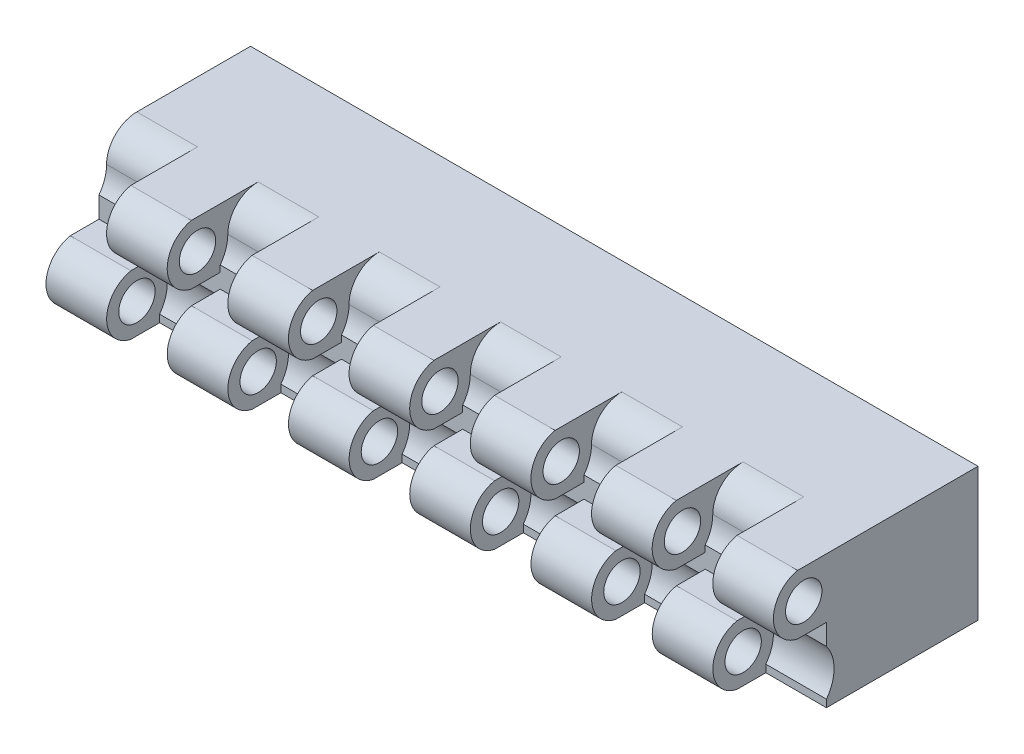
SolidWorks part; units mm, degrees
ref_plane "Front Plane" through (0, 0, 0) normal (0, 0, 1) x (1, 0, 0)
ref_plane "Top Plane" through (0, 0, 0) normal (0, 1, 0) x (1, 0, 0)
ref_plane "Right Plane" through (0, 0, 0) normal (1, 0, 0) x (0, 0, -1)
sketch "Sketch1" plane through (0, 0, 0) normal (1, 0, 0) x (0, 0, -1)
  line L1 (-12.5, 11) -> (12.5, 11)
  line L2 (-12.5, 11) -> (-12.5, -11)
  line L3 (-12.5, -11) -> (12.5, -11)
  line L4 (12.5, 11) -> (12.5, -11)
  line L5 (-12.5, 11) -> (12.5, -11) construction
  line L6 (-12.5, -11) -> (12.5, 11) construction
  point P0 (0, 0)
  dimension "D1" = 22
  dimension "D2" = 25
extrude "Boss-Extrude1" add sketch "Sketch1" along normal mid plane 120
sketch "Sketch5" plane through (60, 0, 0) normal (1, 0, 0) x (0, 0, -1)
  line L0 (-12.5, 11) -> (-12.5, 1.01) construction
  line L1 (-12.5, 11) -> (-12.5, -11) construction
  line L2 (-12.5, 6.005) -> (-17.5, 6.005) construction
  line L3 (-13.7433, 11) -> (-11.25, 11)
  line L7 (-11.25, 6.005) -> (-11.25, 11)
  arc A1 (-13.7433, 11) -> (-11.25, 6.005) centre (-17.5, 6.005) ccw
  dimension "D1" = 5
extrude "Cut-Extrude2" cut sketch "Sketch5" against normal up to next
sketch "Sketch6" plane through (-60, 0, 0) normal (-1, 0, 0) x (0, 0, 1)
  line L0 (12.5, -11) -> (12.5, -1.01) construction
  line L1 (12.5, 2.255) -> (12.5, -11) construction
  line L2 (12.5, -6.005) -> (17.5, -6.005) construction
  circle A0 centre (17.5, -6.005) radius 6.26
  dimension "D2" = 5
  dimension "D1" = 9.99
extrude "Cut-Extrude3" cut sketch "Sketch6" against normal up to next
fillet "Fillet1" radius 5 1 edges at (0, 11, 11.25)
sketch "Sketch2" plane through (60, 0, 0) normal (1, 0, 0) x (0, 0, -1)
  line L0 (-17.25, 1.202) -> (-6, 1.202)
  line L1 (-12.5, -11) -> (-12.5, 1.202) construction
  line L13 (-6, 11) -> (-6, 1.202)
  line L14 (-17.25, 11) -> (-6, 11)
  line L16 (12.5, 11) -> (-6.25, 11) construction
  arc A1 (-17.25, 11) -> (-17.25, 1.202) centre (-16.25, 6.101) ccw
  circle A2 centre (-16.25, 6.101) radius 3
  dimension "D3" = 6
  dimension "D1" = 10.25
  dimension "D5" = 5
  dimension "D2" = 11.25
  dimension "D4" = 5
extrude "Boss-Extrude2" add sketch "Sketch2" against normal blind 10
pattern_linear "LPattern1" count 6 spacing 20 along (-1, 0, 0) of "Boss-Extrude2"
sketch "Sketch3" plane through (-60, 0, 0) normal (-1, 0, 0) x (0, 0, 1)
  line L0 (10.99, -1.202) -> (17.24, -1.202)
  line L1 (17.24, -11) -> (10.99, -11)
  line L2 (12.5, -11) -> (-12.5, -11) construction
  line L8 (10.99, -11) -> (10.99, -1.202)
  arc A1 (17.24, -11) -> (17.24, -1.202) centre (16.24, -6.101) ccw
  circle A2 centre (16.24, -6.101) radius 3
  arc A3 (12.5, -2.2384) -> (12.5, -9.7716) centre (17.5, -6.005) ccw construction
  point P8 (11.24, -6.005)
  dimension "D3" = 6
  dimension "D4" = 5
  dimension "D6" = 9.798
  dimension "D1" = 6.25
  dimension "D5" = 5
extrude "Boss-Extrude3" add sketch "Sketch3" against normal blind 10
pattern_linear "LPattern2" count 6 spacing 20 along (1, 0, 0) of "Boss-Extrude3"
sketch "Sketch4" plane through (0, 0, -12.5) normal (0, 0, -1) x (-1, 0, 0)
  line L0 (-12.5, 0) -> (12.5, 0) construction
  line L2 (-12.5, -5.5) -> (-15.5, -5.5)
  line L3 (-12.5, -5.5) -> (-12.5, 5.5)
  line L4 (-12.5, 5.5) -> (-15.5, 5.5)
  line L5 (-15.5, -5.5) -> (-15.5, 5.5)
  line L6 (0, -11) -> (0, 11) construction
  line L7 (-60, -11) -> (60, -11) construction
  line L8 (-60, 11) -> (60, 11) construction
  line L9 (12.5, 5.5) -> (15.5, 5.5)
  line L10 (15.5, -5.5) -> (15.5, 5.5)
  line L11 (12.5, -5.5) -> (15.5, -5.5)
  line L12 (12.5, -5.5) -> (12.5, 5.5)
  circle A0 centre (0, 0) radius 8
  point P6 (0, 0)
  dimension "D1" = 16
  dimension "D2" = 25
  dimension "D3" = 11
  dimension "D4" = 3
extrude "Cut-Extrude1" cut sketch "Sketch4" against normal blind 15
